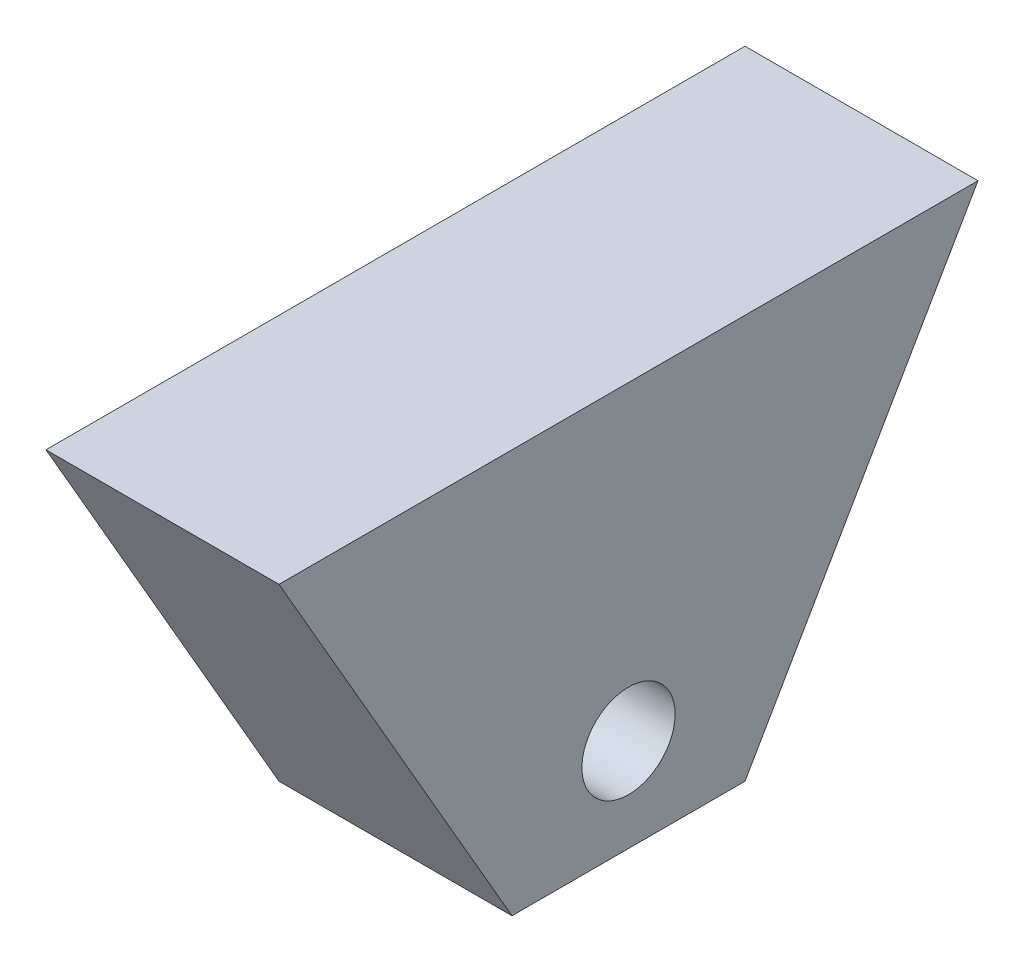
SolidWorks part; units mm, degrees
ref_plane "Front Plane" through (0, 0, 0) normal (0, 0, 1) x (1, 0, 0)
ref_plane "Top Plane" through (0, 0, 0) normal (0, 1, 0) x (1, 0, 0)
ref_plane "Right Plane" through (0, 0, 0) normal (1, 0, 0) x (0, 0, -1)
sketch "Sketch1" plane through (0, 0, 0) normal (1, 0, 0) x (0, 0, -1)
  line L0 (0, 0) -> (150, 0)
  line L1 (150, 0) -> (100, -86.6025)
  line L2 (100, -86.6025) -> (50, -86.6025)
  line L3 (50, -86.6025) -> (0, 0)
  dimension "D1" = 150
  dimension "D2" = 50
  dimension "D3" = 60
  dimension "D4" = 60
extrude "Boss-Extrude1" add sketch "Sketch1" along normal blind 50
sketch "Sketch2" plane through (50, 0, 0) normal (1, 0, 0) x (0, 0, -1)
  line L0 (75, 0) -> (75, -86.6025) construction
  line L1 (150, 0) -> (0, 0) construction
  line L2 (50, -86.6025) -> (100, -86.6025) construction
  circle A0 centre (75, -66.6025) radius 10
  dimension "D1" = 20
  dimension "D2" = 20
extrude "Cut-Extrude1" cut sketch "Sketch2" against normal through all
